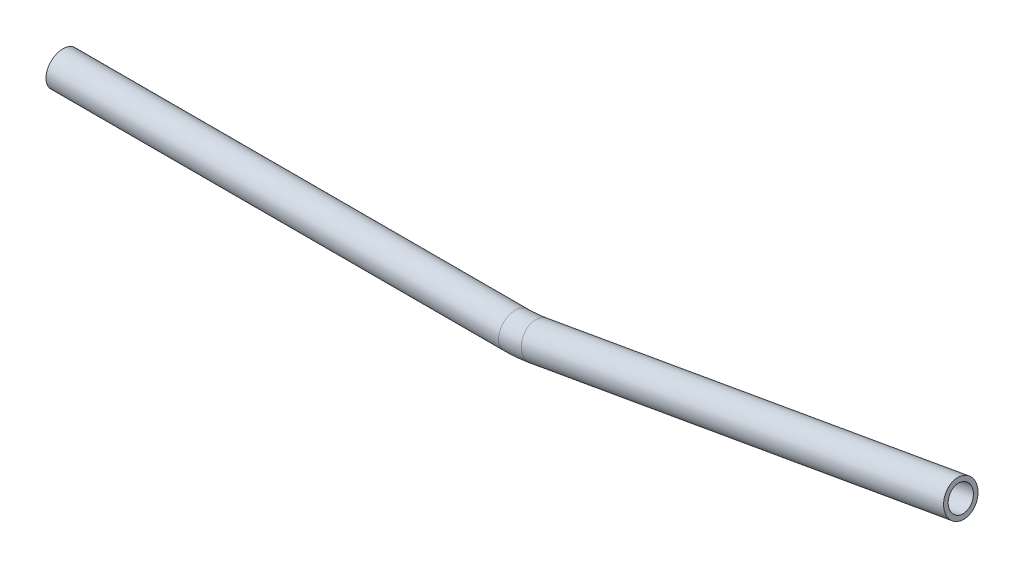
SolidWorks part; units mm, degrees
ref_plane "Front Plane" through (0, 0, 0) normal (0, 0, 1) x (1, 0, 0)
ref_plane "Top Plane" through (0, 0, 0) normal (0, 1, 0) x (1, 0, 0)
ref_plane "Right Plane" through (0, 0, 0) normal (1, 0, 0) x (0, 0, -1)
sketch "Sketch5" plane through (0, 0, 0) normal (0, 0, 1) x (1, 0, 0)
  line L0 (-190.1784, -2.5109) -> (9.8216, -2.5109)
  line L1 (20.319, -1.5925) -> (206.89, 31.305)
  arc A0 (9.8216, -2.5109) -> (20.319, -1.5925) centre (9.8216, 57.941) ccw
  dimension "D2" = 60.4518
  dimension "D1" = 200
  dimension "D5" = 189.4492
  dimension "D3" = 10.5508
  dimension "D4" = 10
ref_plane "Plane1" through (-190.1784, 0, 0) normal (1, 0, 0) x (0, 0, -1)
sketch "Sketch6" plane through (-190.1784, 0, 0) normal (1, 0, 0) x (0, 0, -1)
  circle A0 centre (0, -1.011) radius 5.5
  circle A1 centre (0, -1.011) radius 7.5
  dimension "D1" = 15
  dimension "D2" = 2
sweep "Sweep1" add profiles "Sketch6" path "Sketch5"
equation "\"a\"= \"D3@Sketch5\""
equation "\"D5@Sketch5\"=abs(200-\"a\")"
